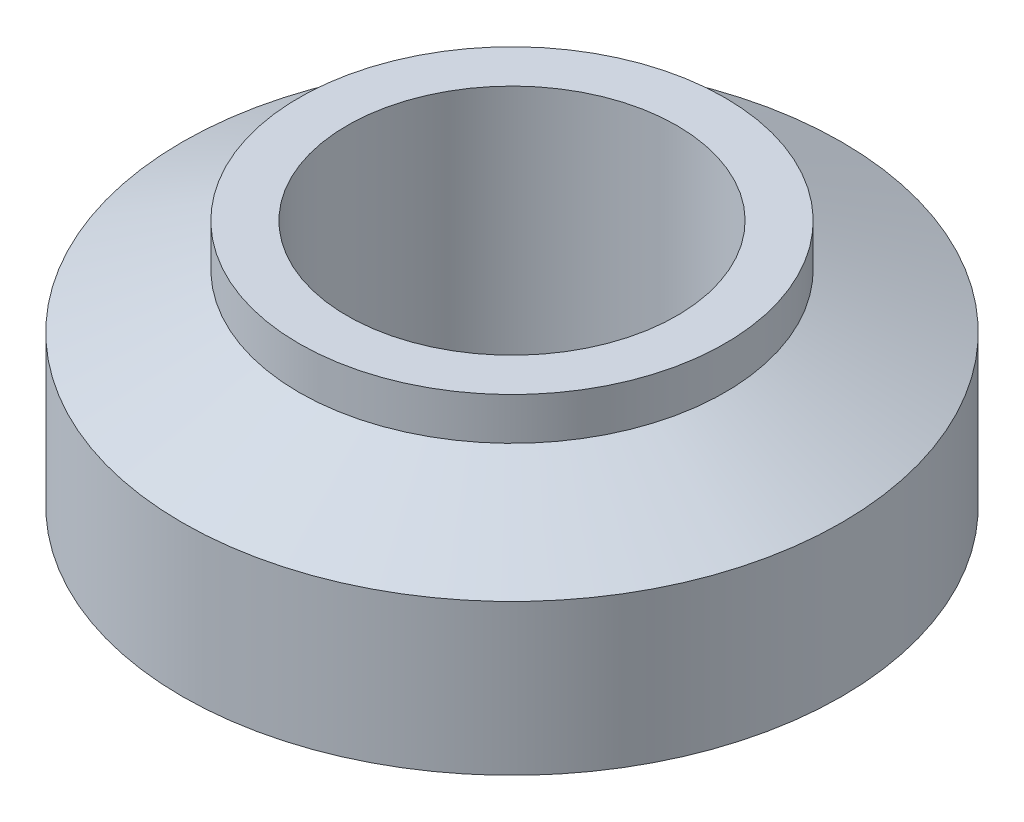
SolidWorks part; units mm, degrees
material "Nylon 6/10"
ref_plane "Front Plane" through (0, 0, 0) normal (0, 0, 1) x (1, 0, 0)
ref_plane "Top Plane" through (0, 0, 0) normal (0, 1, 0) x (1, 0, 0)
ref_plane "Right Plane" through (0, 0, 0) normal (1, 0, 0) x (0, 0, -1)
sketch "Sketch1" plane through (0, 0, 0) normal (1, 0, 0) x (0, 0, -1)
  line L0 (0, 0) -> (0, 9741.1505) construction
  line L1 (-1.66, -2.0011) -> (1.66, -2.0011) construction
  line L2 (1, -3.5011) -> (1, 0.2261) construction
  line L4 (1.292, -2.2575) -> (2, -2.5877)
  line L5 (2, -2.5877) -> (2, -3.5011)
  line L6 (2, -3.5011) -> (1, -3.5011)
  line L7 (1, -3.5011) -> (1, -2.2575)
  line L8 (0, 0) -> (-1.0988, -2.3564) construction
  line L9 (-0.6588, 2.5152) -> (2.3502, 1.1121) construction
  line L10 (-4.773, 0.5706) -> (4.4188, -3.7156) construction
  line L11 (4.4188, -3.7156) -> (5.6866, -0.9967) construction
  line L12 (5.6866, -0.9967) -> (-3.5051, 3.2895) construction
  line L13 (-3.5051, 3.2895) -> (-4.773, 0.5706) construction
  line L14 (-2.5598, -0.4614) -> (-1.292, 2.2575) construction
  line L15 (1.292, -2.2575) -> (2.5598, 0.4614) construction
  line L16 (1.292, -2.2575) -> (1.292, -2.0011)
  line L17 (1.292, -2.0011) -> (1, -2.0011)
  line L18 (1, -2.0011) -> (1, -2.2575)
  circle A1 centre (0, 0) radius 2.6 construction
  point P16 (0.8457, 1.8136)
  dimension "D6" = 2
  dimension "D8" = 25
  dimension "D2" = 5.2
  dimension "D3" = 3.32
  dimension "D4" = 1
  dimension "D5" = 1.5
  dimension "D9" = 3.32
  dimension "D10" = 1.5
  dimension "D11" = 3
  dimension "D12" = 2.125
  dimension "D13" = 4.25
revolve "Revolve1" add sketch "Sketch1" angle 360 about L0
